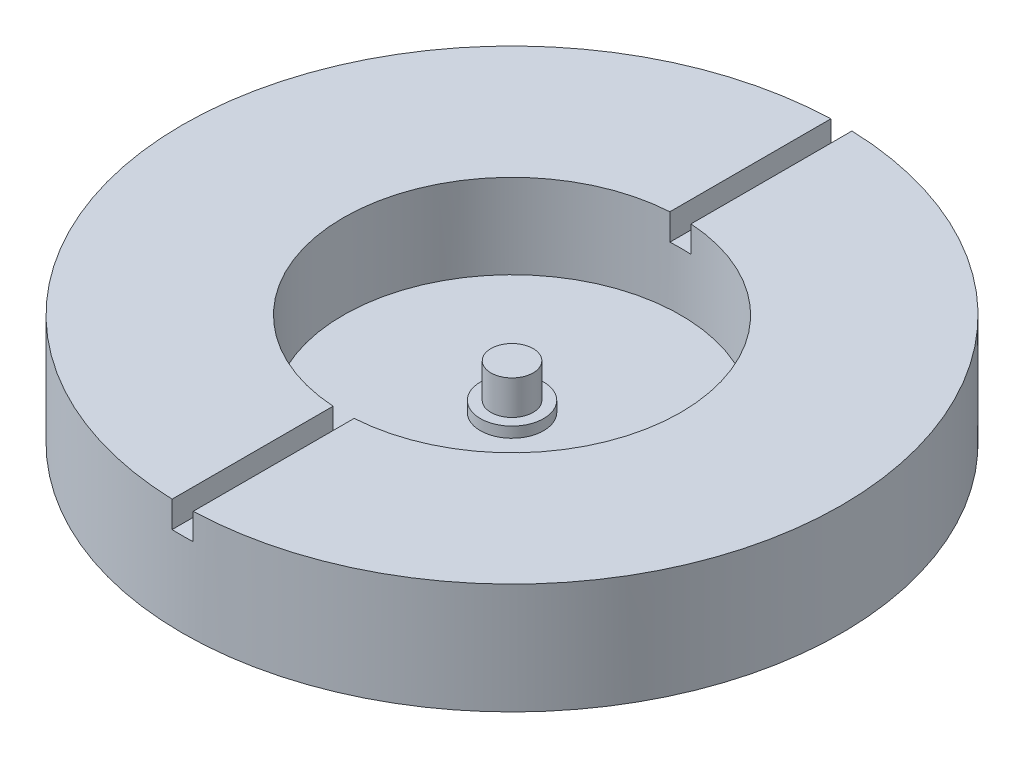
SolidWorks part; units mm, degrees
ref_plane "Front Plane" through (0, 0, 0) normal (0, 0, 1) x (1, 0, 0)
ref_plane "Top Plane" through (0, 0, 0) normal (0, 1, 0) x (1, 0, 0)
ref_plane "Right Plane" through (0, 0, 0) normal (1, 0, 0) x (0, 0, -1)
sketch "Sketch1" plane through (0, 0, 0) normal (0, 1, 0) x (1, 0, 0)
  circle A0 centre (0, 0) radius 62.5
  dimension "D1" = 125
extrude "Boss-Extrude1" add sketch "Sketch1" along normal blind 21
sketch "Sketch2" plane through (0, 21, 0) normal (0, 1, 0) x (1, 0, 0)
  circle A0 centre (0, 0) radius 32
  circle A1 centre (0, 0) radius 6
  dimension "D1" = 64
extrude "Cut-Extrude1" cut sketch "Sketch2" against normal blind 16
sketch "Sketch3" plane through (0, 21, 0) normal (0, 1, 0) x (1, 0, 0)
  circle A0 centre (0, 0) radius 6
  circle A1 centre (0, 0) radius 4
extrude "Cut-Extrude2" cut sketch "Sketch3" against normal blind 14
sketch "Sketch4" plane through (0, 21, 0) normal (0, 1, 0) x (1, 0, 0)
  circle A0 centre (0, 0) radius 4
extrude "Cut-Extrude3" cut sketch "Sketch4" against normal blind 7.5
sketch "Sketch5" plane through (0, 21, 0) normal (0, 1, 0) x (1, 0, 0)
  line L0 (0, 0) -> (2, 0) construction
  line L1 (0, 0) -> (-2, 0) construction
  line L2 (2, 62.468) -> (2, -62.468)
  line L3 (-2, 62.468) -> (-2, -62.468)
  circle A0 centre (0, 0) radius 62.5 construction
  arc A1 (-2, -62.468) -> (2, -62.468) centre (0, 0) ccw
  arc A2 (2, 62.468) -> (-2, 62.468) centre (0, 0) ccw
  dimension "D1" = 2
  dimension "D2" = 2
extrude "Cut-Extrude4" cut sketch "Sketch5" against normal blind 5
